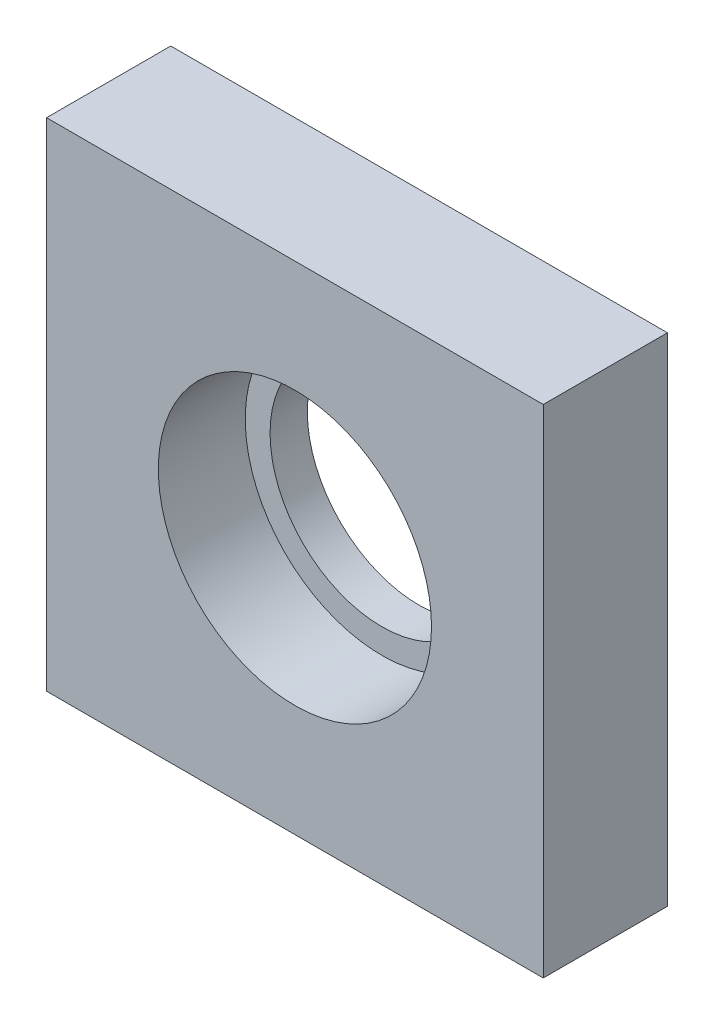
SolidWorks part; units mm, degrees
material "3.3535 (EN-AW 5754)"
ref_plane "Plan1" through (0, 0, 0) normal (0, 0, 1) x (1, 0, 0)
ref_plane "Plan2" through (0, 0, 0) normal (0, 1, 0) x (1, 0, 0)
ref_plane "Plan3" through (0, 0, 0) normal (1, 0, 0) x (0, 0, -1)
sketch "Esquisse1" plane through (0, 0, 0) normal (0, 0, 1) x (1, 0, 0)
  line L0 (-22.3607, -20) -> (22.3607, -20)
  arc A0 (22.3607, -20) -> (-22.3607, -20) centre (0, 0) ccw
  dimension "D1" = 60
  dimension "D2" = 20
  dimension "D3" = 44.7214
extrude "Base-Extrusion" add sketch "Esquisse1" along normal blind 10
sketch "Esquisse2" plane through (0, 0, 10) normal (0, 0, 1) x (1, 0, 0)
  circle A0 centre (0, 0) radius 11
  dimension "D1" = 22
extrude "Enlèv. mat.-Extru.1" cut sketch "Esquisse2" against normal blind 7
sketch "Esquisse3" plane through (0, 0, 0) normal (0, 0, -1) x (-1, 0, 0)
  circle A0 centre (0, 0) radius 9
  dimension "D1" = 18
extrude "Enlèv. mat.-Extru.2" cut sketch "Esquisse3" against normal through all
sketch "Esquisse4" plane through (0, 0, 10) normal (0, 0, 1) x (1, 0, 0)
  line L2 (20, -20) -> (-20, -20)
  line L3 (20, -20) -> (20, 20)
  line L4 (20, 20) -> (-20, 20)
  line L5 (-20, -20) -> (-20, 20)
  dimension "D1" = 40
  dimension "D2" = 20
  dimension "D3" = 40
  dimension "D4" = 20
extrude "Enlèv. mat.-Extru.3" cut sketch "Esquisse4" against normal through all flip side to cut
hole_wizard "Perçage1" positions "Esquisse6" profile "Esquisse5" tap size "M4x0.7" standard "ISO"
sketch "Esquisse6" plane through (0, -20, 0) normal (0, -1, 0) x (1, 0, 0)
  point P0 (15, 5)
  dimension "D1" = 5
  dimension "D2" = 15
sketch "Esquisse5" plane through (15, -20, 5) normal (1, 0, 0) x (0, 0, -1)
  line L0 (0, 0) -> (0, 30.9914)
  line L1 (0, 30.9914) -> (1.65, 30)
  line L2 (1.65, 30) -> (1.65, 0)
  line L5 (1.65, 0) -> (0, 0)
  line L10 (0, 30.9914) -> (-1.65, 30) construction
  line L11 (0, -6.35) -> (0, 107.95) construction
  dimension "Diamètre du perçage" = 3.3
  dimension "Profondeur du perçage" = 30
  dimension "Angle de pointe" = 118
cosmetic thread "Représentation de filetage1" parameters "D1"=25, "D2"=4
pattern_linear "Répétition linéaire1" count 2 spacing 30 along (-1, 0, 0) of "Perçage1"
